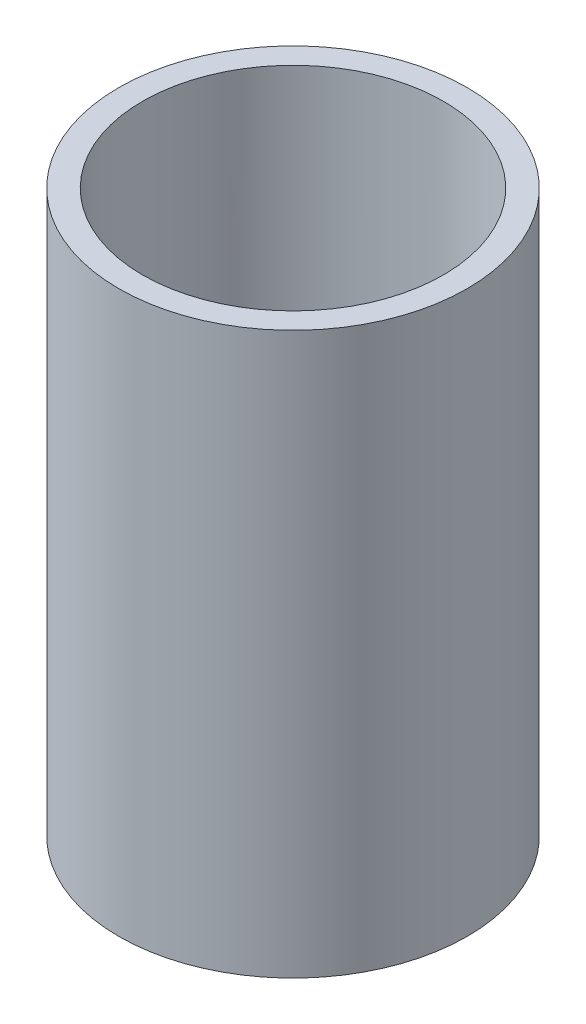
SolidWorks part; units mm, degrees
ref_plane "Front Plane" through (0, 0, 0) normal (0, 0, 1) x (1, 0, 0)
ref_plane "Top Plane" through (0, 0, 0) normal (0, 1, 0) x (1, 0, 0)
ref_plane "Right Plane" through (0, 0, 0) normal (1, 0, 0) x (0, 0, -1)
sketch "Sketch1" plane through (0, 0, 0) normal (0, 1, 0) x (1, 0, 0)
  circle A0 centre (0, 0) radius 18.35
  dimension "D1" = 36.7
extrude "Boss-Extrude1" add sketch "Sketch1" along normal blind 59.1
sketch "Sketch2" plane through (0, 59.1, 0) normal (0, 1, 0) x (1, 0, 0)
  circle A0 centre (0, 0) radius 15.85
  dimension "D1" = 31.7
extrude "Cut-Extrude1" cut sketch "Sketch2" against normal blind 57.1
sketch "Sketch3" plane through (0, 0, 0) normal (0, 0, 1) x (1, 0, 0)
  line L0 (-15.85, 33.7) -> (15.85, 2)
  line L9 (-15.85, 33.7) -> (-15.85, 2)
  line L10 (-15.85, 2) -> (15.85, 2)
  line L12 (15.85, 59.1) -> (-15.85, 59.1) construction
  point P1 (0, 0)
  point P2 (15.2565, 1.1893)
  point P7 (0, 0)
  point P10 (0, 0)
  point P11 (0, 0)
  point P13 (0, 0)
  dimension "D1" = 25.4
  dimension "D2" = 57.1
  dimension "D3" = 31.7
extrude "Boss-Extrude2" add sketch "Sketch3" along normal up to next and the other way up to next
